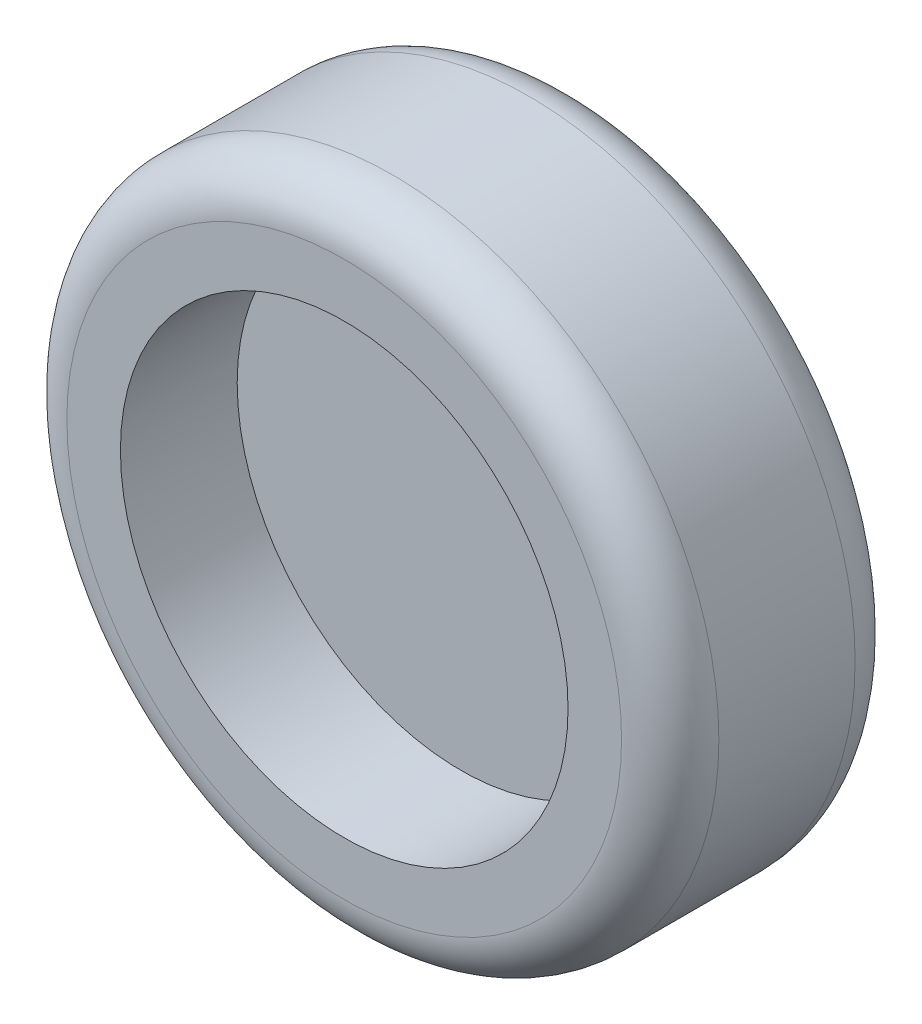
SolidWorks part; units mm, degrees
ref_plane "Plan de face" through (0, 0, 0) normal (0, 0, 1) x (1, 0, 0)
ref_plane "Plan de dessus" through (0, 0, 0) normal (0, 1, 0) x (1, 0, 0)
ref_plane "Plan de droite" through (0, 0, 0) normal (1, 0, 0) x (0, 0, -1)
sketch "Esquisse1" plane through (0, 0, 0) normal (0, 0, 1) x (1, 0, 0)
  circle A0 centre (0, 0) radius 33.5
  dimension "D1" = 67
extrude "Boss.-Extru.1" add sketch "Esquisse1" along normal blind 24
fillet "Congé1" radius 5 1 edges at (33.5, 0, 24)
fillet "Congé2" radius 5 1 edges at (33.5, 0, 0)
sketch "Esquisse2" plane through (0, 0, 24) normal (0, 0, 1) x (1, 0, 0)
  circle A0 centre (0, 0) radius 23
extrude "Enlèv. mat.-Extru.1" cut sketch "Esquisse2" against normal blind 12
